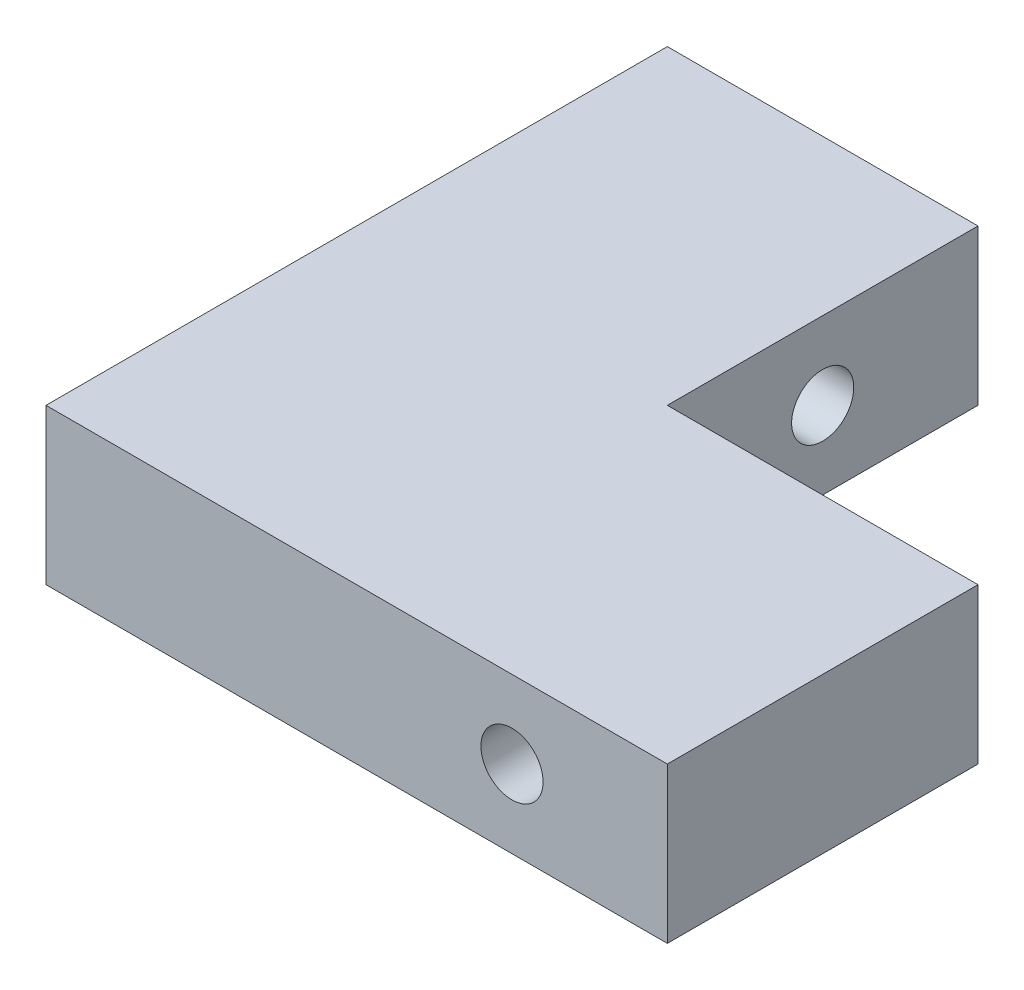
SolidWorks part; units mm, degrees
ref_plane "Plano frontal" through (0, 0, 0) normal (0, 0, 1) x (1, 0, 0)
ref_plane "Plano superior" through (0, 0, 0) normal (0, 1, 0) x (1, 0, 0)
ref_plane "Plano direito" through (0, 0, 0) normal (1, 0, 0) x (0, 0, -1)
sketch "Esboço1" plane through (0, 0, 0) normal (0, 1, 0) x (1, 0, 0)
  line L0 (-70, 36.3043) -> (-70, -43.6957)
  line L1 (-70, -43.6957) -> (10, -43.6957)
  line L2 (10, -43.6957) -> (10, -3.6957)
  line L3 (10, -3.6957) -> (-30, -3.6957)
  line L4 (-30, -3.6957) -> (-30, 36.3043)
  line L5 (-30, 36.3043) -> (-70, 36.3043)
  dimension "D1" = 40
  dimension "D2" = 40
  dimension "D3" = 40
extrude "Ressalto-extrusão1" add sketch "Esboço1" along normal blind 20 contours L0 L1 L2 L3 L4 L5
sketch "Esboço3" plane through (-30, 0, 0) normal (1, 0, 0) x (0, 0, -1)
  line L0 (36.3043, 10) -> (-3.6957, 10) construction
  line L1 (36.3043, 20) -> (36.3043, 0) construction
  line L2 (-3.6957, 20) -> (-3.6957, 0) construction
  circle A0 centre (16.3043, 10) radius 4
  dimension "D1" = 8
sketch "Esboço4" plane through (0, 0, 3.6957) normal (0, 0, -1) x (-1, 0, 0)
  line L0 (30, 10) -> (-10, 10) construction
  line L1 (-10, 20) -> (-10, 0) construction
  circle A0 centre (10, 10) radius 4
  dimension "D1" = 8
extrude "Corte-extrusão1" cut sketch "Esboço3" against normal through all
extrude "Corte-extrusão2" cut sketch "Esboço4" against normal through all
